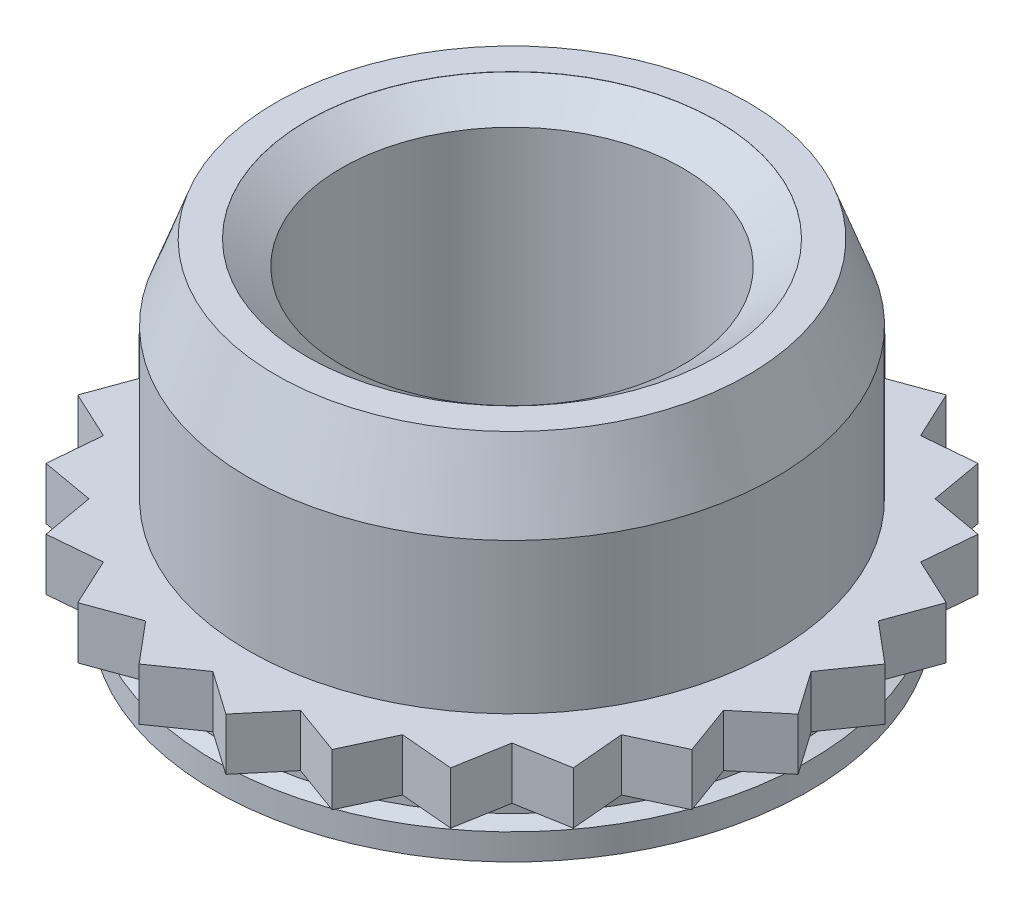
SolidWorks part; units mm, degrees
revolve "Body" add sketch "BodySke"
sketch "BodySke" plane through (0, 0, 0) normal (0, 0, 1) x (1, 0, 0)
  line L0 (4.1372, -1.0682) -> (4.1372, -0.765)
  line L1 (3.86, 2.2) -> (3.4596, 3.3)
  line L2 (4.87, 0) -> (3.86, 0)
  line L3 (2.5, 3.3) -> (2.5, -1.53)
  line L4 (2.5, -1.53) -> (4.355, -1.53)
  line L5 (4.355, -1.53) -> (4.355, -1.1475)
  line L6 (4.355, -1.1475) -> (4.1372, -1.0682)
  line L7 (1.016, 1) -> (3.86, 1) construction
  line L8 (3.86, 0) -> (3.86, 2.2)
  line L9 (0, 0) -> (0, 15.24) construction
  line L11 (3.4596, 3.3) -> (2.5, 3.3)
  line L15 (4.1372, -0.765) -> (4.87, -0.765)
  line L16 (4.87, -0.765) -> (4.87, 0)
  dimension "Clinch_dia" = 9.74
  dimension "C_dia" = 8.71
  dimension "Thread_min" = 5
  dimension "Advance" = 1
  dimension "D_dia" = 7.72
  dimension "Height" = 3.3
  dimension "A_ht" = 1.53
  dimension "Clinching_ht" = 0.765
  dimension "Groove_dia" = 8.2745
  dimension "Chamfer_ht" = 1.1
  dimension "D1" = 20
  dimension "D2" = 70
  dimension "C_len" = 0.3825
cosmetic thread "ThreadCosmetic" [suppressed]
revolve "EndChamfer" cut sketch "EndChamferSke" angle 360 about L0
sketch "EndChamferSke" plane through (0, 0, 0) normal (0, 0, 1) x (1, 0, 0)
  line L0 (0, -2.54) -> (0, 7.62) construction
  line L1 (0, 0) -> (0, 15.24) construction
  line L2 (3, -1.784) -> (3, -1.5275)
  line L3 (3, -1.5275) -> (2.5, -1.1775)
  line L4 (2.5, -1.1775) -> (2.5, -1.784)
  line L5 (2.5, -1.784) -> (3, -1.784)
  line L6 (3, 3.2975) -> (3, 3.554)
  line L7 (3, 3.554) -> (2.5, 3.554)
  line L8 (2.5, 3.554) -> (2.5, 2.9475)
  line L9 (2.5, 2.9475) -> (3, 3.2975)
  line L10 (3.4596, 3.3) -> (-3.4596, 3.3) construction
  line L11 (-4.355, -1.53) -> (4.355, -1.53) construction
  line L12 (2.5, 3.3) -> (-2.5, 3.3) construction
  dimension "Thread_min" = 5
  dimension "D1" = 0.254
  dimension "D2" = 34.99
  dimension "Thread_nominal" = 6
  dimension "D3" = 0.254
ref_plane "Plane1" through (0, 0, 0) normal (0, 0, 1) x (1, 0, 0)
ref_plane "Plane2" through (0, 0, 0) normal (0, 1, 0) x (1, 0, 0)
ref_plane "Plane3" through (0, 0, 0) normal (1, 0, 0) x (0, 0, -1)
ref_plane "Plane4" through (0, -0.5486, 0) normal (0, 1, 0) x (-1, 0, 0)
sketch "ThdSchSke" plane through (0, 0, 0) normal (0, 0, 1) x (1, 0, 0)
  line L0 (0, -5.08) -> (0, 7.62) construction
  line L1 (0, 0) -> (0, 15.24) construction
  line L2 (0, -1.5275) -> (3, -1.5275) construction
  line L4 (3, -1.5275) -> (2.5, -1.1774)
  line L6 (3, -1.5275) -> (2.5, -1.8776)
  line L7 (2.5, -1.1774) -> (2.5, -1.8776)
  line L8 (3, -1.5275) -> (-3, -1.5275) construction
  dimension "Thread_min" = 5
  dimension "Thread_nominal" = 6
revolve "ThreadSchematic" [suppressed] cut sketch "ThdSchSke" angle 360 about L0
pattern_linear "ThdSchPat" [suppressed]
sketch "CliRinCutSke" plane through (0, -0.765, 0) normal (0, -1, 0) x (1, 0, 0)
  line L0 (0.6357, 4.8283) -> (0, 4.383)
  line L1 (0, 4.383) -> (-0.6357, 4.8283)
  line L2 (0, 0) -> (0, 5.842) construction
  arc A1 (0.6357, 4.8283) -> (-0.6357, 4.8283) centre (0, 0) ccw
  circle A2 centre (0, 0) radius 4.383 construction
  dimension "Angle" = 15
  dimension "Clinch_dia" = 9.74
  dimension "Clinch_minor" = 8.766
extrude "ClinchCut" cut sketch "CliRinCutSke" against normal blind 0.765
pattern_circular "ClinchCutPat" count 24 every 15 about axis through (0, 0, 0) along (0, 1, 0) of "ClinchCut"
equation "' \"A_ht@BodySke\" = 1.53"
equation "' \"D_dia@BodySke\" = 7.72"
equation "' \"C_dia@BodySke\" = 8.71"
equation "' \"Height@BodySke\" = 3.3"
equation "' \"Clinch_dia@BodySke\" = 9.74"
equation "' \"Advance@BodySke\" = 1"
equation "' \"Thread_min@BodySke\" = 5"
equation "' \"Thread_nominal@ThreadCosmetic\" = 6"
equation "\"Count@ClinchCutPat\" = 24"
equation "\"Angle@ClinchCutPat\" = 360 / \"Count@ClinchCutPat\""
equation "\"Angle@CliRinCutSke\" = 360 / \"Count@ClinchCutPat\""
equation "\"Clinch_dia@CliRinCutSke\" = \"Clinch_dia@BodySke\""
equation "\"Clinch_minor@CliRinCutSke\" = \"Clinch_dia@BodySke\" * 0.9"
equation "\"C_len@BodySke\" = \"A_ht@BodySke\" * 0.25"
equation "\"Groove_dia@BodySke\" = \"C_dia@BodySke\" * 0.95"
equation "\"Clinching_ht@BodySke\" = \"A_ht@BodySke\" * 0.5"
equation "\"Depth@ClinchCut\" =  \"A_ht@BodySke\" * 0.5"
equation "\"Chamfer_ht@BodySke\" = \"Height@BodySke\" / 3"
equation "\"Thread_nominal@EndChamferSke\" = \"Thread_nominal@ThreadCosmetic\""
equation "\"Thread_min@EndChamferSke\" = \"Thread_min@BodySke\""
equation "\"D2@EndChamferSke\" = \"Vee_angle@ThdSchSke\" / 2 - 0.01"
equation "\"Thread_nominal@ThdSchSke\" = \"Thread_nominal@ThreadCosmetic\""
equation "\"Thread_min@ThdSchSke\" = \"Thread_min@BodySke\""
equation "\"Num_threads@ThdSchPat\" = int(  ( \"Height@BodySke\" + \"A_ht@BodySke\" - \"Inset@EndChamferSke\" - \"Inset_far@EndChamferSke\" ) / \"Advance@BodySke\" + 0.999 )  + 1"
equation "\"Advance@ThdSchPat\" = ( \"Height@BodySke\" + \"A_ht@BodySke\" - \"Inset@EndChamferSke\" - \"Inset_far@EndChamferSke\" ) /  (\"Num_threads@ThdSchPat\" - 1) 'relax it"
